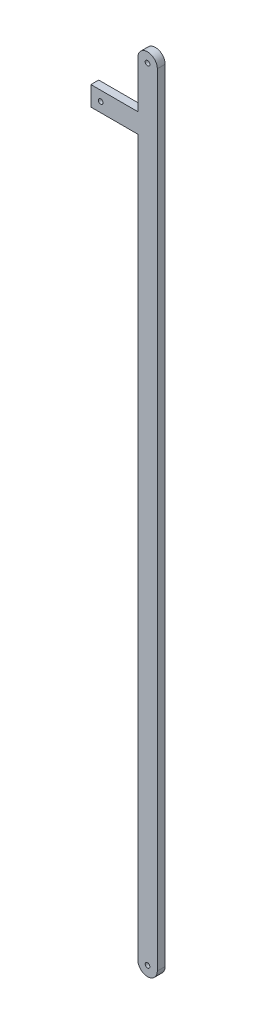
SolidWorks part; units mm, degrees
ref_plane "Front Plane" through (0, 0, 0) normal (0, 0, 1) x (1, 0, 0)
ref_plane "Top Plane" through (0, 0, 0) normal (0, 1, 0) x (1, 0, 0)
ref_plane "Right Plane" through (0, 0, 0) normal (1, 0, 0) x (0, 0, -1)
sketch "Sketch1" plane through (0, 0, 0) normal (0, 0, 1) x (1, 0, 0)
  line L0 (-12.5, 0) -> (-12.5, -60)
  line L1 (12.5, 0) -> (12.5, -1000)
  line L2 (-12.5, -500) -> (12.5, -500) construction
  line L4 (-72.5, -60) -> (-72.5, -85)
  line L5 (-72.5, -85) -> (-12.5, -85)
  line L6 (-12.5, 0) -> (12.5, 0) construction
  line L7 (-12.5, -85) -> (-12.5, -1000)
  line L8 (-72.5, -60) -> (-47.5, -60) construction
  line L9 (-60, -60) -> (-60, -85) construction
  line L10 (-72.5, -60) -> (-12.5, -60)
  circle A0 centre (0, 0) radius 3
  arc A1 (12.5, 0) -> (-12.5, 0) centre (0, 0) ccw
  arc A2 (12.5, -1000) -> (-12.5, -1000) centre (0, -1000) cw
  circle A3 centre (0, -1000) radius 3
  circle A4 centre (-60, -72.5) radius 3
  point P20 (-60, -52.5)
  point P21 (-61.672, -55.6227)
  dimension "D1" = 6
  dimension "D2" = 25
  dimension "D6" = 6
  dimension "D3" = 1000
  dimension "D4" = 60
  dimension "D5" = 60
extrude "Boss-Extrude1" add sketch "Sketch1" along normal blind 10
